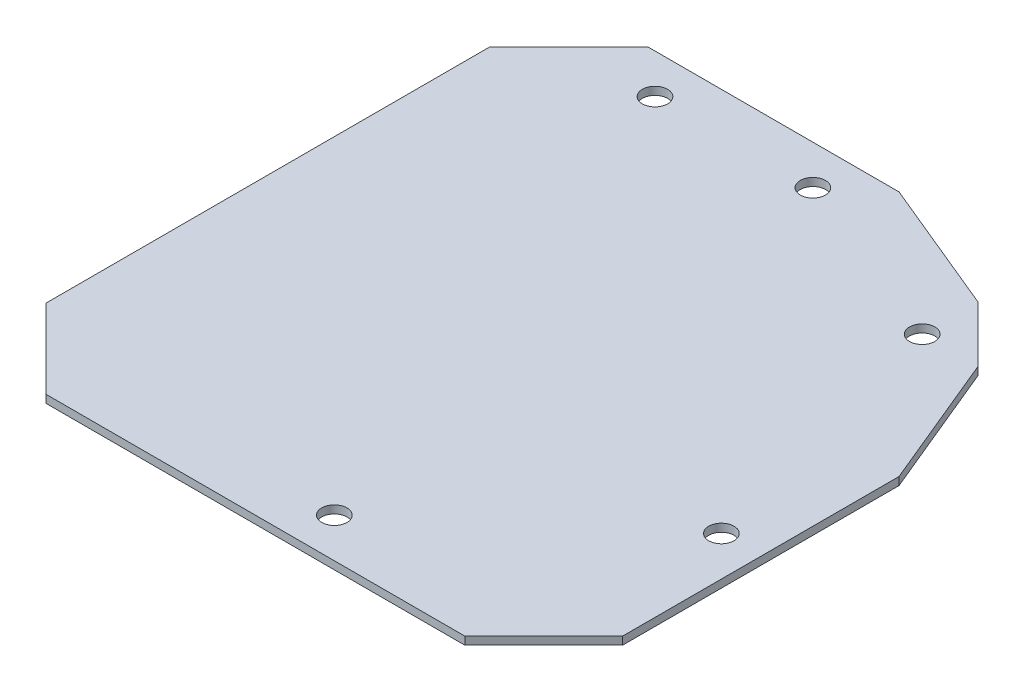
SolidWorks part; units mm, degrees
ref_plane "前视基准面" through (0, 0, 0) normal (0, 0, 1) x (1, 0, 0)
ref_plane "上视基准面" through (0, 0, 0) normal (0, 1, 0) x (1, 0, 0)
ref_plane "右视基准面" through (0, 0, 0) normal (1, 0, 0) x (0, 0, -1)
other "Configuration Table"
sketch "草图1" plane through (0, 0, 0) normal (0, 1, 0) x (1, 0, 0)
  line L0 (0, 0) -> (53.033, 0)
  line L1 (53.033, 0) -> (53.033, 55)
  line L2 (53.033, 55) -> (0, 108.033)
  line L3 (0, 108.033) -> (0, 0)
  dimension "D1" = 45
  dimension "D2" = 75
  dimension "D3" = 55
extrude "凸台-拉伸1" add sketch "草图1" along normal blind 1
sketch "草图2" plane through (0, 0, 0) normal (0, -1, 0) x (1, 0, 0)
  line L15 (53.033, -55) -> (0, -108.033) construction
  line L16 (0, -108.033) -> (31.8198, -108.033)
  line L17 (0, -108.033) -> (0, -76.2132)
  line L18 (0, -76.2132) -> (31.8198, -76.2132)
  line L19 (31.8198, -108.033) -> (31.8198, -76.2132)
  dimension "D1" = 30
extrude "切除-拉伸1" cut sketch "草图2" against normal blind 10
chamfer "倒角1" distance 10 distance2 10 3 edges at (53.033, 0.5, 0) (53.033, 0.5, -55) (31.8198, 0.5, -76.2132)
sketch "草图4" plane through (0, 1, 0) normal (0, 1, 0) x (1, 0, 0)
  line L0 (38.8909, 62.0711) -> (42.4264, 65.6066) construction
  line L1 (45.9619, 62.0711) -> (38.8909, 69.1421) construction
  line L2 (48.033, 27.5) -> (53.033, 27.5) construction
  line L3 (53.033, 10) -> (53.033, 45) construction
  line L4 (21.5165, 0) -> (21.5165, 5) construction
  line L5 (0, 0) -> (43.033, 0) construction
  circle A0 centre (38.8909, 62.0711) radius 1.6
  circle A1 centre (48.033, 27.5) radius 1.6
  circle A2 centre (21.5165, 5) radius 1.6
  dimension "D1" = 3.2
  dimension "D3" = 3.2
  dimension "D6" = 3.2
  dimension "D2" = 5
  dimension "D4" = 5
  dimension "D5" = 5
extrude "切除-拉伸3" cut sketch "草图4" against normal blind 10
sketch "草图5" plane through (0, 0, 0) normal (0, -1, 0) x (1, 0, 0)
  line L1 (-20, 0) -> (0, 0)
  line L2 (-20, 0) -> (-20, -76.2132)
  line L3 (-20, -76.2132) -> (0, -76.2132)
  line L4 (0, 0) -> (0, -76.2132)
  dimension "D1" = 20
extrude "凸台-拉伸2" add sketch "草图5" against normal up to surface (1 mm away) up to face at (38.8909, 1, -60.4711)
chamfer "倒角2" distance 10 angle 45 2 edges at (-20, 0.5, 0) (-20, 0.5, -76.2132)
sketch "草图6" plane through (0, 0, 0) normal (0, -1, 0) x (1, 0, 0)
  line L0 (15.9099, -71.2132) -> (-4.0901, -71.2132) construction
  line L1 (5.9099, -71.2132) -> (5.9099, -76.2132) construction
  line L2 (21.8198, -76.2132) -> (-10, -76.2132) construction
  circle A0 centre (15.9099, -71.2132) radius 1.6
  circle A1 centre (-4.0901, -71.2132) radius 1.6
  dimension "D2" = 3.2
  dimension "D3" = 5
  dimension "D1" = 20
extrude "切除-拉伸4" cut sketch "草图6" against normal blind 10
